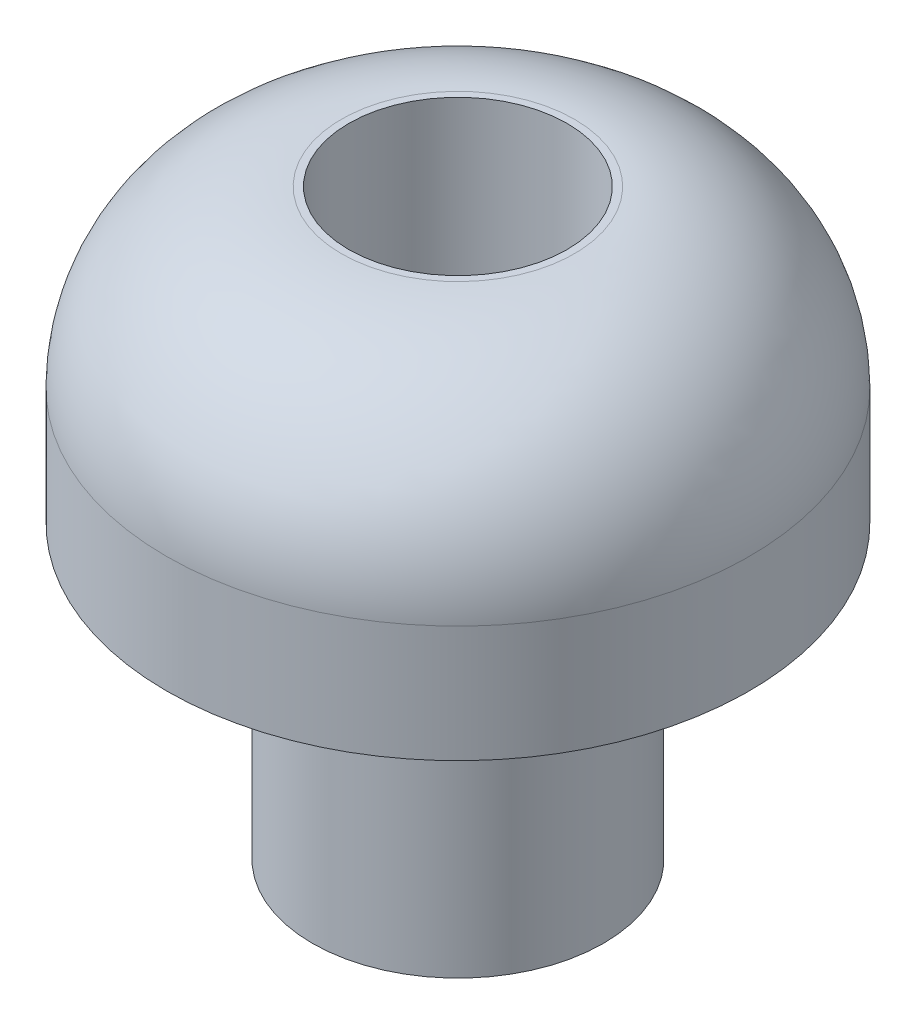
SolidWorks part; units mm, degrees
ref_plane "Płaszczyzna przednia" through (0, 0, 0) normal (0, 0, 1) x (1, 0, 0)
ref_plane "Płaszczyzna górna" through (0, 0, 0) normal (0, 1, 0) x (1, 0, 0)
ref_plane "Płaszczyzna prawa" through (0, 0, 0) normal (1, 0, 0) x (0, 0, -1)
sketch "Szkic1" plane through (0, 0, 0) normal (0, 1, 0) x (1, 0, 0)
  circle A0 centre (0, 0) radius 10
  dimension "D1" = 20
extrude "Dodanie-wyciągnięcie1" add sketch "Szkic1" along normal blind 10
fillet "Zaokrąglenie1" radius 6 1 edges at (0, 10, 10)
sketch "Szkic2" plane through (0, 0, 0) normal (0, -1, 0) x (1, 0, 0)
  circle A0 centre (0, 0) radius 5
  dimension "D1" = 10
extrude "Dodanie-wyciągnięcie2" add sketch "Szkic2" along normal blind 10
sketch "Szkic3" plane through (0, 10, 0) normal (0, 1, 0) x (1, 0, 0)
  circle A0 centre (0, 0) radius 3.75
  dimension "D1" = 7.5
extrude "Wytnij-wyciągnięcie1" cut sketch "Szkic3" against normal offset from surface (8 mm away) 2 up to face at (0, 0, -5)
sketch "Szkic4" plane through (0, -10, 0) normal (0, -1, 0) x (1, 0, 0)
  circle A0 centre (0, 0) radius 1.6
  dimension "D1" = 3.2
extrude "Wytnij-wyciągnięcie2" cut sketch "Szkic4" against normal up to next
